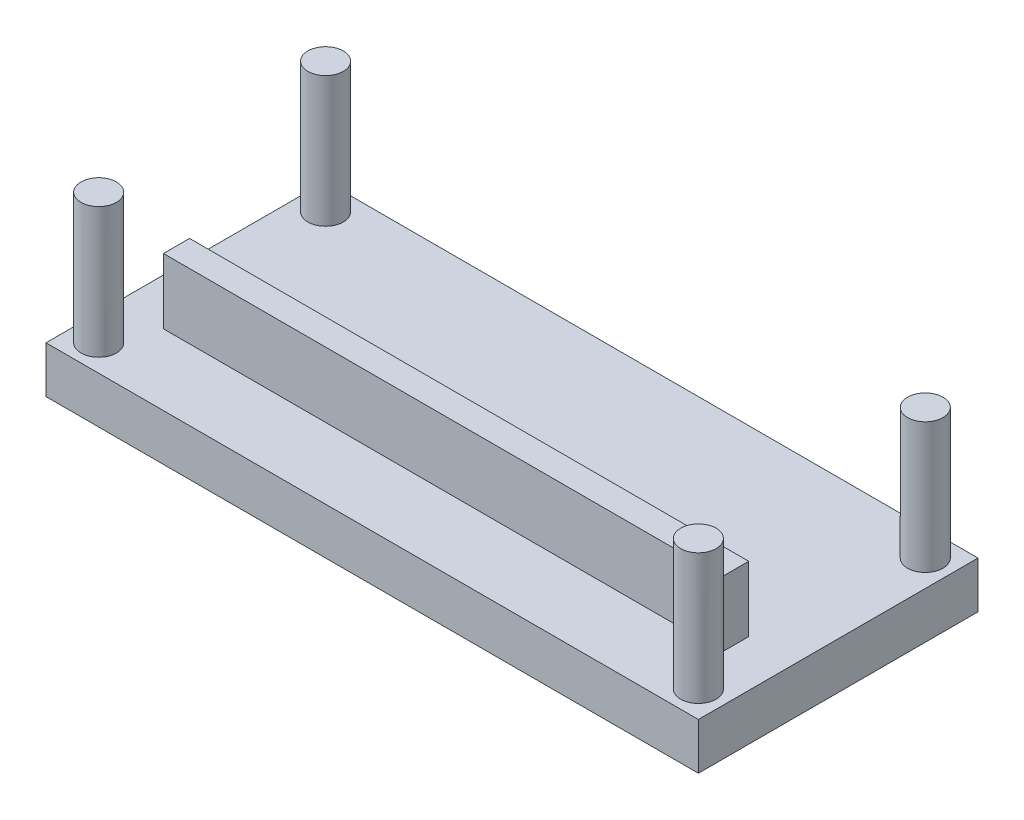
SolidWorks part; units mm, degrees
ref_plane "Front Plane" through (0, 0, 0) normal (0, 0, 1) x (1, 0, 0)
ref_plane "Top Plane" through (0, 0, 0) normal (0, 1, 0) x (1, 0, 0)
ref_plane "Right Plane" through (0, 0, 0) normal (1, 0, 0) x (0, 0, -1)
sketch "Sketch1" plane through (0, 0, 0) normal (0, 1, 0) x (1, 0, 0)
  line L0 (0, 0) -> (0, 30)
  line L1 (0, 30) -> (70, 30)
  line L2 (70, 30) -> (70, 0)
  line L3 (70, 0) -> (0, 0)
extrude "Boss-Extrude1" add sketch "Sketch1" along normal blind 15
sketch "Sketch2" plane through (0, 15, 0) normal (0, 1, 0) x (1, 0, 0)
  circle A0 centre (2.8284, 2.8284) radius 2
  circle A1 centre (2.8284, 27.1716) radius 2
  circle A2 centre (67.1716, 27.1716) radius 2
  circle A3 centre (67.1716, 2.8284) radius 2
sketch "Sketch3" plane through (0, 15, 0) normal (0, 1, 0) x (1, 0, 0)
  line L0 (65, 7.6) -> (70, 7.6)
  line L2 (65, 7.6) -> (65, 10.4)
  line L4 (70, 0) -> (70, 30) construction
  line L5 (65, 10.4) -> (5, 10.4)
  line L7 (5, 10.4) -> (5, 7.6)
  line L8 (5, 7.6) -> (65, 7.6)
extrude "Boss-Extrude3" add sketch "Sketch3" along normal blind 7 contours L2 L5 L7 L8
sketch "Sketch4" plane through (0, 0, 0) normal (0, -1, 0) x (-1, 0, 0)
  line L0 (0, 0) -> (0, 30)
  line L1 (0, 30) -> (-70, 30)
  line L2 (-70, 30) -> (-70, 0)
  line L3 (-70, 0) -> (0, 0)
extrude "Cut-Extrude1" cut sketch "Sketch4" against normal blind 10
sketch "Sketch5" plane through (0, 15, 0) normal (0, 1, 0) x (1, 0, 0)
  circle A0 centre (2.8284, 2.8284) radius 1.9
  circle A1 centre (2.8284, 27.1716) radius 1.9
  circle A2 centre (67.1716, 27.1716) radius 1.9
  circle A3 centre (67.1716, 2.8284) radius 1.9
extrude "Boss-Extrude4" add sketch "Sketch5" along normal blind 14
